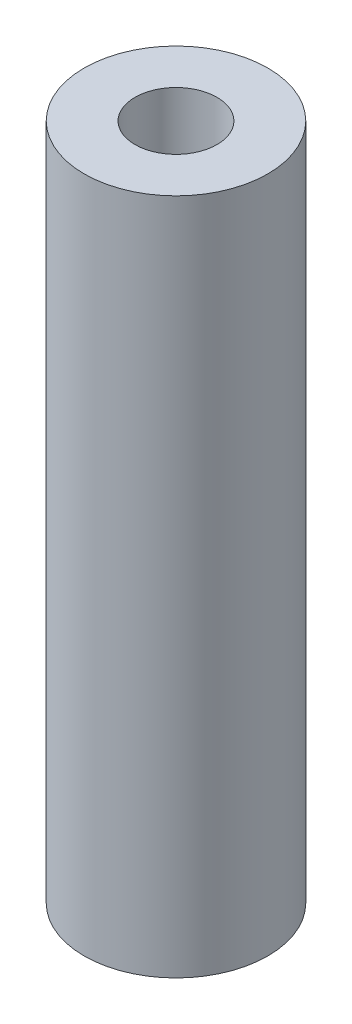
SolidWorks part; units mm, degrees
ref_plane "Front Plane" through (0, 0, 0) normal (0, 0, 1) x (1, 0, 0)
ref_plane "Top Plane" through (0, 0, 0) normal (0, 1, 0) x (1, 0, 0)
ref_plane "Right Plane" through (0, 0, 0) normal (1, 0, 0) x (0, 0, -1)
sketch "Sketch1" plane through (0, 0, 0) normal (0, 1, 0) x (1, 0, 0)
  circle A0 centre (0, 0) radius 4.8404
  circle A1 centre (0, 0) radius 10.8404
  dimension "D1" = 6
extrude "Boss-Extrude1" add sketch "Sketch1" along normal blind 80
